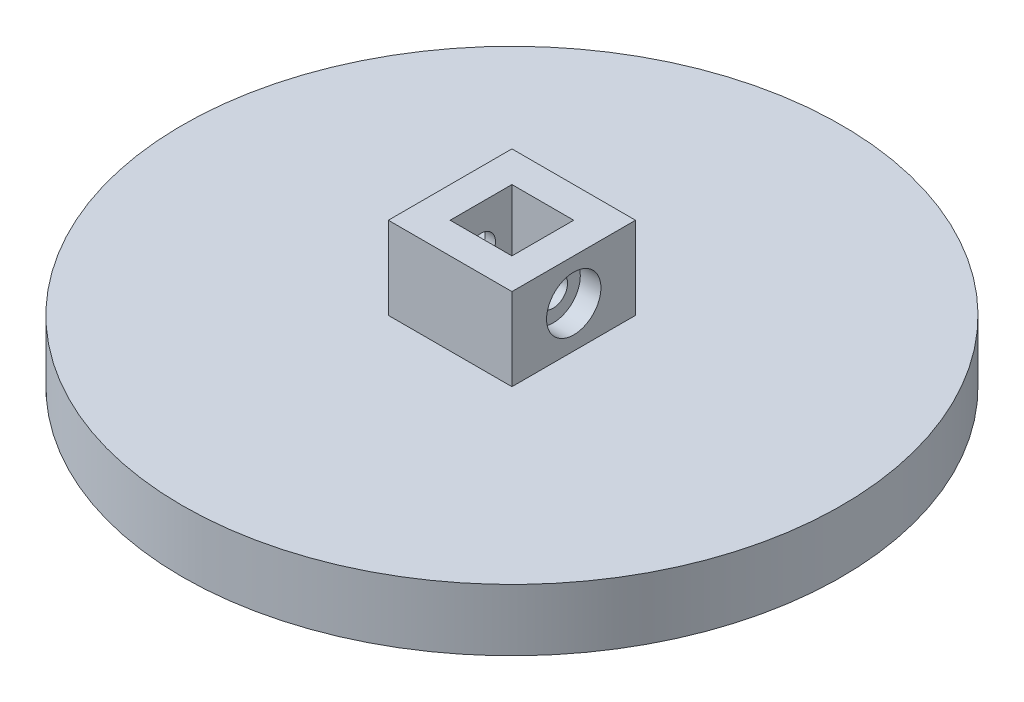
SolidWorks part; units mm, degrees
ref_plane "Front Plane" through (0, 0, 0) normal (0, 0, 1) x (1, 0, 0)
ref_plane "Top Plane" through (0, 0, 0) normal (0, 1, 0) x (1, 0, 0)
ref_plane "Right Plane" through (0, 0, 0) normal (1, 0, 0) x (0, 0, -1)
sketch "Sketch1" plane through (0, 0, 0) normal (0, 1, 0) x (1, 0, 0)
  circle A0 centre (0, 0) radius 40
extrude "Boss-Extrude1" add sketch "Sketch1" along normal blind 7.5
sketch "Sketch2" plane through (0, 7.5, 0) normal (0, 1, 0) x (1, 0, 0)
  line L7 (-7.5, -7.5) -> (7.5, -7.5)
  line L8 (-7.5, -7.5) -> (-7.5, 7.5)
  line L9 (-7.5, 7.5) -> (7.5, 7.5)
  line L10 (7.5, -7.5) -> (7.5, 7.5)
  point P1 (0, 0)
  point P6 (0, 0)
  dimension "D3" = 15
extrude "Boss-Extrude2" add sketch "Sketch2" along normal blind 10
sketch "Sketch3" plane through (7.5, 0, 0) normal (1, 0, 0) x (0, 0, -1)
  line L0 (-7.5, 17.5) -> (7.5, 17.5) construction
  circle A0 centre (0, 12.5) radius 1.75
  dimension "D1" = 5
extrude "Cut-Extrude1" cut sketch "Sketch3" against normal up to surface (15 mm away) up to face at (-7.5, 12.5, 0)
sketch "Sketch4" plane through (7.5, 0, 0) normal (1, 0, 0) x (0, 0, -1)
  circle A0 centre (0, 12.5) radius 3.3
extrude "Cut-Extrude2" cut sketch "Sketch4" against normal blind 2.5
sketch "Sketch5" plane through (-7.5, 0, 0) normal (-1, 0, 0) x (0, 0, 1)
  line L1 (-3.35, 12.5) -> (-1.675, 9.5988)
  line L2 (-1.675, 9.5988) -> (1.675, 9.5988)
  line L3 (1.675, 9.5988) -> (3.35, 12.5)
  line L4 (3.35, 12.5) -> (1.675, 15.4012)
  line L5 (1.675, 15.4012) -> (-1.675, 15.4012)
  line L6 (-1.675, 15.4012) -> (-3.35, 12.5)
  circle A1 centre (0, 12.5) radius 3.35 construction
extrude "Cut-Extrude3" cut sketch "Sketch5" against normal blind 2.5
sketch "Sketch6" plane through (0, 17.5, 0) normal (0, 1, 0) x (1, 0, 0)
  line L1 (-3.75, -3.75) -> (3.75, -3.75)
  line L2 (-3.75, -3.75) -> (-3.75, 3.75)
  line L3 (-3.75, 3.75) -> (3.75, 3.75)
  line L4 (3.75, -3.75) -> (3.75, 3.75)
  line L5 (-3.75, -3.75) -> (3.75, 3.75) construction
  line L6 (-3.75, 3.75) -> (3.75, -3.75) construction
  point P0 (0, 0)
  dimension "D1" = 7.5
  dimension "D2" = 7.5
extrude "Cut-Extrude4" cut sketch "Sketch6" against normal up to surface (17.5 mm away) up to face at (0, 0, 40)
